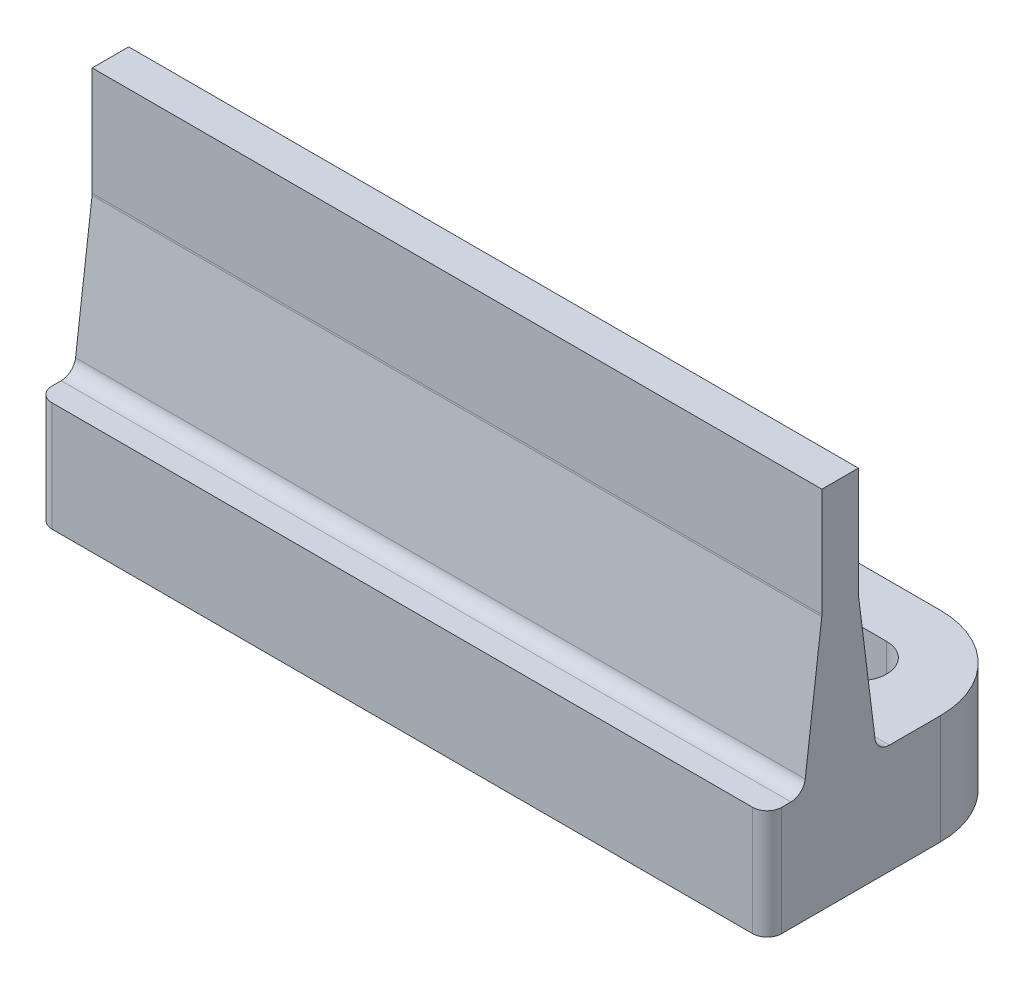
SolidWorks part; units mm, degrees
material "ABS"
ref_plane "Front Plane" through (0, 0, 0) normal (0, 0, 1) x (1, 0, 0)
ref_plane "Top Plane" through (0, 0, 0) normal (0, 1, 0) x (1, 0, 0)
ref_plane "Right Plane" through (0, 0, 0) normal (1, 0, 0) x (0, 0, -1)
sketch "Sketch1" plane through (0, 0, 0) normal (1, 0, 0) x (0, 0, -1)
  line L0 (-4, 0) -> (10.5, 0)
  line L1 (10.5, 0) -> (10.5, 6)
  line L2 (10.5, 6) -> (2, 6)
  line L4 (1, 20) -> (-1, 20)
  line L6 (-2, 6) -> (-4, 6)
  line L7 (-4, 6) -> (-4, 0)
  line L8 (0, 13.2) -> (0, -13.2) construction
  line L9 (2, 6) -> (1, 14)
  line L10 (1, 14) -> (1, 20)
  line L11 (-1, 20) -> (-1, 14)
  line L13 (-1, 14) -> (-2, 6)
  point P8 (0, 20)
  dimension "D1" = 10.5
  dimension "D2" = 6
  dimension "D3" = 4
  dimension "D4" = 20
  dimension "D5" = 2
  dimension "D6" = 6
  dimension "D7" = 4
extrude "Boss-Extrude1" add sketch "Sketch1" along normal mid plane 40
sketch "Sketch4" plane through (0, 6, 0) normal (0, 1, 0) x (1, 0, 0)
  line L0 (-15, 6) -> (-5, 6) construction
  line L1 (-15, 7.55) -> (-5, 7.55)
  line L2 (-15, 4.45) -> (-5, 4.45)
  line L3 (5, 6) -> (15, 6) construction
  line L4 (5, 7.55) -> (15, 7.55)
  line L5 (5, 4.45) -> (15, 4.45)
  line L6 (5, 6) -> (-5, 6) construction
  line L7 (0, -7.975) -> (0, 7.975) construction
  arc A0 (-15, 7.55) -> (-15, 4.45) centre (-15, 6) ccw
  arc A1 (-5, 4.45) -> (-5, 7.55) centre (-5, 6) ccw
  arc A2 (5, 7.55) -> (5, 4.45) centre (5, 6) ccw
  arc A3 (15, 4.45) -> (15, 7.55) centre (15, 6) ccw
  point P2 (-10, 6)
  point P7 (10, 6)
  point P15 (0, 6)
  dimension "D1" = 3.1
  dimension "D2" = 6
  dimension "D3" = 10
  dimension "D4" = 20
extrude "Cut-Extrude1" cut sketch "Sketch4" against normal up to next
fillet "Fillet1" radius 5 2 edges at (20, 3, -10.5) (-20, 3, -10.5)
fillet "Fillet2" radius 0.7937 6 edges at (20, 3, 4) (-20, 3, 4) (0, 6, -2) (0, 14, -1) (0, 14, 1) (0, 6, 2)
